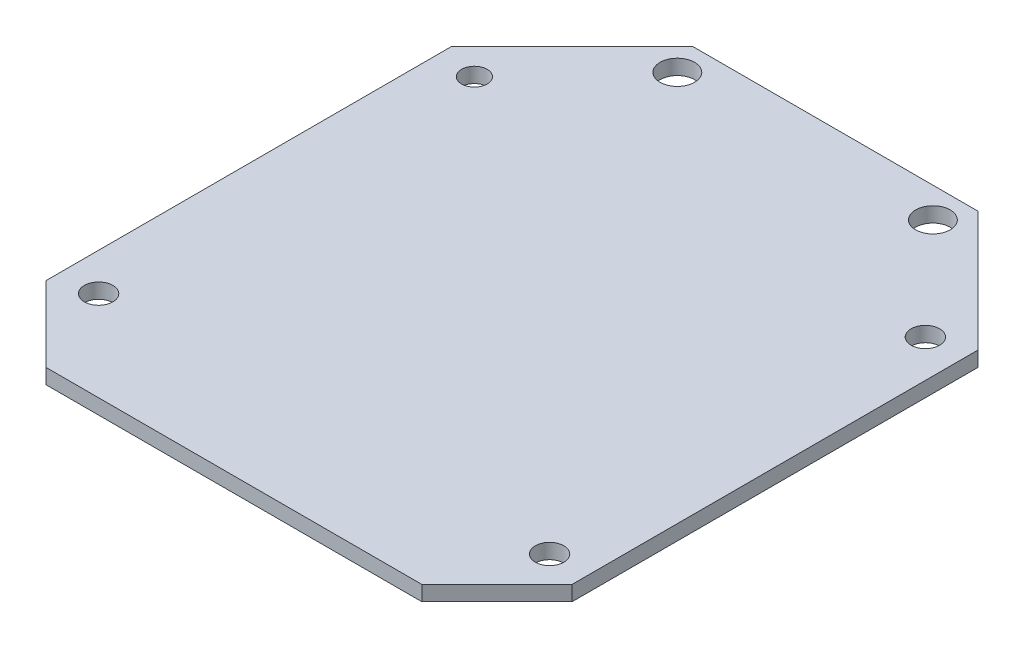
SolidWorks part; units mm, degrees
ref_plane "Front Plane" through (0, 0, 0) normal (0, 0, 1) x (1, 0, 0)
ref_plane "Top Plane" through (0, 0, 0) normal (0, 1, 0) x (1, 0, 0)
ref_plane "Right Plane" through (0, 0, 0) normal (1, 0, 0) x (0, 0, -1)
sketch "Sketch1" plane through (0, 0, 0) normal (0, 1, 0) x (1, 0, 0)
  line L0 (30, -6.8901) -> (5, -6.8901)
  line L1 (5, -6.8901) -> (0, -1.8901)
  line L2 (0, -1.8901) -> (0, 25.1099)
  line L3 (0, 25.1099) -> (8, 33.1099)
  line L4 (8, 33.1099) -> (27, 33.1099)
  line L5 (27, 33.1099) -> (35, 25.1099)
  line L6 (35, 25.1099) -> (35, -1.8901)
  line L7 (35, -1.8901) -> (30, -6.8901)
  dimension "D1" = 135
  dimension "D2" = 5
  dimension "D3" = 5
  dimension "D4" = 135
  dimension "D5" = 8
  dimension "D6" = 8
  dimension "D7" = 25
  dimension "D8" = 27
extrude "Boss-Extrude1" add sketch "Sketch1" along normal blind 1
sketch "Sketch2" plane through (0, 1, 0) normal (0, 1, 0) x (1, 0, 0)
  line L0 (0, 25.1099) -> (0, -1.8901) construction
  line L1 (35, -1.8901) -> (35, 25.1099) construction
  line L2 (5, -6.8901) -> (30, -6.8901) construction
  line L3 (27, 33.1099) -> (8, 33.1099) construction
  circle A0 centre (32.5, -0.8901) radius 0.95
  circle A1 centre (2.5, -0.8901) radius 0.95
  circle A2 centre (32.5, 24.1099) radius 0.95
  circle A3 centre (2.5, 24.1099) radius 0.85
  dimension "D1" = 1.9
  dimension "D2" = 1.9
  dimension "D3" = 1.9
  dimension "D4" = 1.7
  dimension "D5" = 2.5
  dimension "D6" = 2.5
  dimension "D7" = 2.5
  dimension "D8" = 2.5
  dimension "D9" = 6
  dimension "D10" = 6
  dimension "D11" = 9
  dimension "D12" = 9
extrude "Cut-Extrude1" cut sketch "Sketch2" against normal blind 1
sketch "Sketch3" plane through (0, 1, 0) normal (0, 1, 0) x (1, 0, 0)
  line L0 (27, 33.1099) -> (8, 33.1099) construction
  line L1 (0, 25.1099) -> (0, -1.8901) construction
  line L2 (35, -1.8901) -> (35, 25.1099) construction
  circle A0 centre (26, 31.1099) radius 1.15
  circle A1 centre (9, 31.1099) radius 1.15
  dimension "D1" = 2.3
  dimension "D2" = 2.3
  dimension "D3" = 2
  dimension "D4" = 2
  dimension "D5" = 9
  dimension "D6" = 9
extrude "Cut-Extrude2" cut sketch "Sketch3" against normal blind 1
